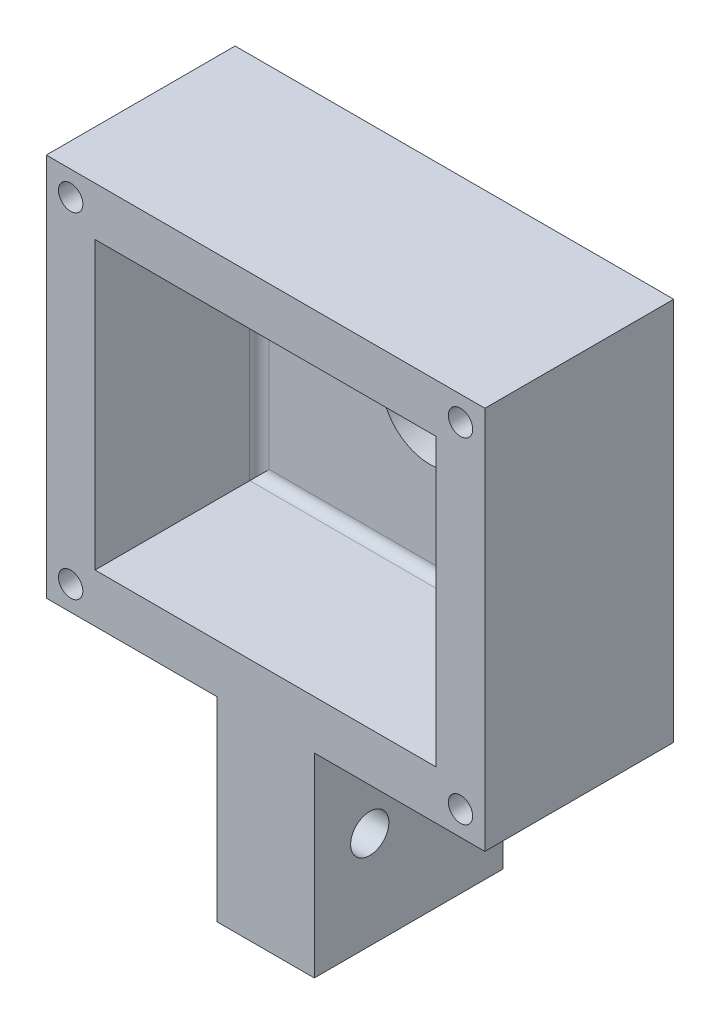
SolidWorks part; units mm, degrees
ref_plane "Front Plane" through (0, 0, 0) normal (0, 0, 1) x (1, 0, 0)
ref_plane "Top Plane" through (0, 0, 0) normal (0, 1, 0) x (1, 0, 0)
ref_plane "Right Plane" through (0, 0, 0) normal (1, 0, 0) x (0, 0, -1)
sketch "Sketch1" plane through (0, 0, 0) normal (0, 0, 1) x (1, 0, 0)
  line L1 (22.225, -18.6531) -> (-22.225, -18.6531)
  line L2 (22.225, -18.6531) -> (22.225, 18.6531)
  line L3 (22.225, 18.6531) -> (-22.225, 18.6531)
  line L4 (-22.225, -18.6531) -> (-22.225, 18.6531)
  line L5 (22.225, -18.6531) -> (-22.225, 18.6531) construction
  line L6 (22.225, 18.6531) -> (-22.225, -18.6531) construction
  line L7 (28.575, -25.0031) -> (-28.575, -25.0031)
  line L8 (28.575, -25.0031) -> (28.575, 25.0031)
  line L9 (28.575, 25.0031) -> (-28.575, 25.0031)
  line L10 (-28.575, -25.0031) -> (-28.575, 25.0031)
  line L11 (28.575, -25.0031) -> (-28.575, 25.0031) construction
  line L12 (28.575, 25.0031) -> (-28.575, -25.0031) construction
  point P0 (0, 0)
  point P6 (0, 0)
  dimension "D1" = 6.35
  dimension "D2" = 6.35
  dimension "D3" = 44.45
  dimension "D4" = 37.3062
extrude "Boss-Extrude1" add sketch "Sketch1" along normal blind 21.4312
sketch "Sketch2" plane through (0, 0, 0) normal (0, 0, 1) x (1, 0, 0)
  line L1 (28.575, -25.0031) -> (-28.575, -25.0031)
  line L2 (28.575, -25.0031) -> (28.575, 25.0031)
  line L3 (28.575, 25.0031) -> (-28.575, 25.0031)
  line L4 (-28.575, -25.0031) -> (-28.575, 25.0031)
  line L5 (28.575, -25.0031) -> (-28.575, 25.0031) construction
  line L6 (28.575, 25.0031) -> (-28.575, -25.0031) construction
  circle A0 centre (0, 0) radius 6.35
  point P0 (0, 0)
  dimension "D1" = 12.7
extrude "Boss-Extrude2" add sketch "Sketch2" against normal blind 3.175
fillet "Fillet1" radius 1.27 4 edges at (0, -18.6531, 0) (22.225, 0, 0) (0, 18.6531, 0) (-22.225, 0, 0)
sketch "Sketch6" plane through (0, 0, 21.4312) normal (0, 0, 1) x (1, 0, 0)
  line L0 (-28.575, 21.8281) -> (28.575, 21.8281) construction
  line L1 (-28.575, 25.0031) -> (-28.575, -25.0031) construction
  line L2 (28.575, -25.0031) -> (28.575, 25.0031) construction
  line L3 (26.9875, -21.8281) -> (-26.9875, -21.8281) construction
  line L6 (28.575, 25.0031) -> (-28.575, 25.0031) construction
  line L7 (25.4, 21.8281) -> (25.4, -21.8281) construction
  line L8 (25.4, -21.8281) -> (24.196, -20.7934) construction
  line L9 (-25.4, 21.8281) -> (-25.4, -21.8281) construction
  line L10 (-28.575, -25.0031) -> (28.575, -25.0031) construction
  line L11 (-24.196, 20.7934) -> (-25.4, 21.8281) construction
  circle A0 centre (-25.4, 21.8281) radius 1.5875
  circle A1 centre (25.4, 21.8281) radius 1.5875
  circle A2 centre (25.4, -21.8281) radius 1.5875
  circle A3 centre (-25.4, -21.8281) radius 1.5875
  dimension "D2" = 3.175
  dimension "D4" = 3.175
  dimension "D1" = 3.175
  dimension "D3" = 3.175
  dimension "D5" = 3.175
extrude "Cut-Extrude2" cut sketch "Sketch6" against normal blind 9.525
sketch "Sketch7" plane through (0, -25.0031, 0) normal (0, -1, 0) x (1, 0, 0)
  line L0 (-28.575, -3.175) -> (28.575, -3.175) construction
  line L1 (-6.35, -3.175) -> (6.35, -3.175)
  line L2 (-6.35, -3.175) -> (-6.35, 21.4312)
  line L3 (-6.35, 21.4312) -> (6.35, 21.4312)
  line L4 (6.35, -3.175) -> (6.35, 21.4312)
  line L5 (-28.575, 21.4312) -> (28.575, 21.4312) construction
  line L6 (28.575, 21.4312) -> (28.575, -3.175) construction
  line L7 (-28.575, 21.4312) -> (-28.575, -3.175) construction
  dimension "D1" = 22.225
  dimension "D2" = 22.225
extrude "Boss-Extrude3" add sketch "Sketch7" along normal blind 25.4
sketch "Sketch8" plane through (-6.35, 0, 0) normal (-1, 0, 0) x (0, 0, 1)
  line L0 (4.0481, -37.7031) -> (-3.175, -37.7031) construction
  line L1 (-3.175, -50.4031) -> (-3.175, -25.0031) construction
  line L2 (4.0481, -37.7031) -> (14.2081, -37.7031) construction
  line L3 (14.2081, -37.7031) -> (21.4312, -37.7031) construction
  line L4 (21.4312, -50.4031) -> (21.4312, -25.0031) construction
  line L5 (21.4312, -50.4031) -> (-3.175, -50.4031) construction
  circle A0 centre (4.0481, -37.7031) radius 2.4892
  circle A1 centre (14.2081, -37.7031) radius 2.4892
  dimension "D1" = 4.9784
  dimension "D2" = 4.9784
  dimension "D3" = 12.7
  dimension "D4" = 10.16
extrude "Cut-Extrude3" cut sketch "Sketch8" against normal up to next
